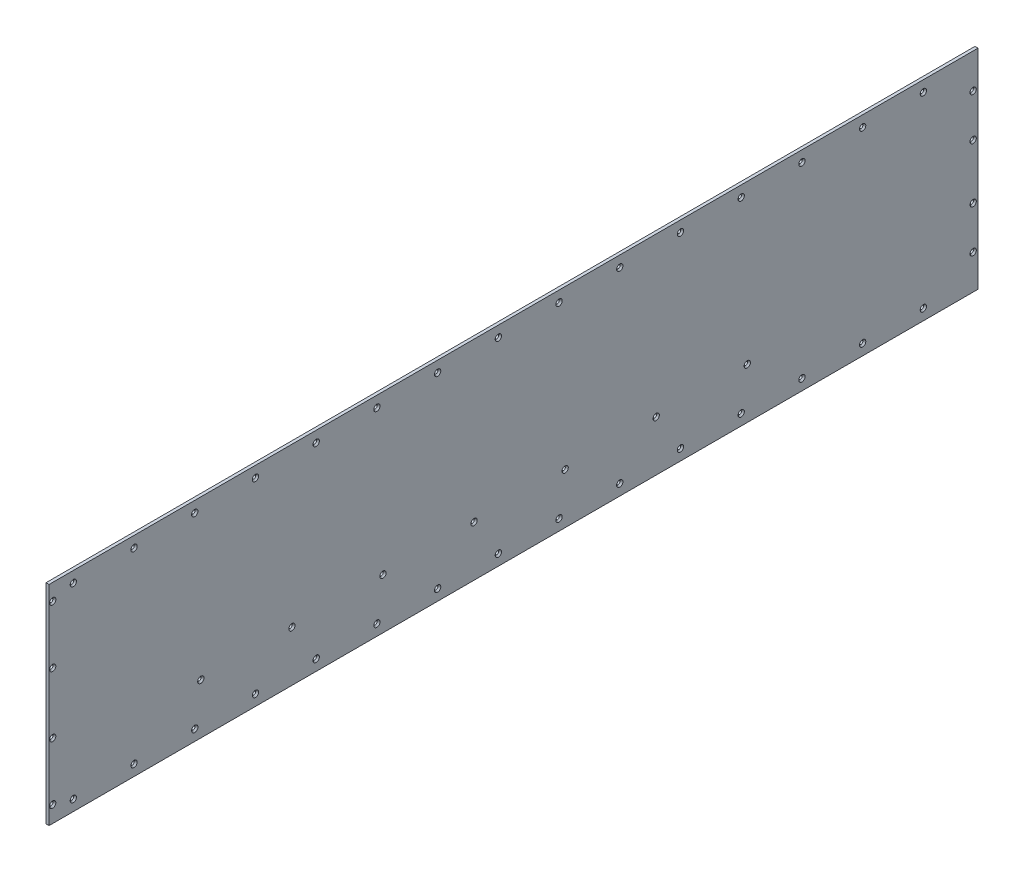
SolidWorks part; units mm, degrees
material "1060 Legierung"
ref_plane "Front Plane" through (0, 0, 0) normal (0, 0, 1) x (1, 0, 0)
ref_plane "Top Plane" through (0, 0, 0) normal (0, 1, 0) x (1, 0, 0)
ref_plane "Right Plane" through (0, 0, 0) normal (1, 0, 0) x (0, 0, -1)
sketch "Sketch1" plane through (0, 0, 0) normal (1, 0, 0) x (0, 0, -1)
  line L0 (0, 0) -> (59.3183, 0) construction
  line L1 (0, 28.1909) -> (0, -28.8956) construction
  line L2 (-765, 172) -> (765, 172)
  line L3 (765, 172) -> (765, -172)
  line L4 (765, -172) -> (-765, -172)
  line L5 (-765, -172) -> (-765, 172)
  dimension "D1" = 1530
  dimension "D2" = 344
extrude "Boss-Extrude1" add sketch "Sketch1" along normal blind 6
chamfer "Fase1" distance 1 angle 45 4 edges at (0, -172, 0) (0, 172, 0) (0, 0, 765) (0, 0, -765)
hole_wizard "CSK for M5 Countersunk Raised Head Screw1" positions "Skizze2" profile "Skizze1" countersink size "M5" standard "DIN" end condition through all
sketch "Skizze2" plane through (6, 0, 0) normal (1, 0, 0) x (0, 0, -1)
  line L0 (802.4859, 0) -> (371.043, 0) construction
  line L2 (765, -172) -> (765, 172) construction
  line L3 (-765, 172) -> (-765, -172) construction
  line L4 (3.3, 0) -> (-3.3, 0) construction
  point P0 (757, 115)
  point P2 (757, 45)
  point P12 (-759, 145)
  point P14 (-759, 50)
  dimension "D1" = 45
  dimension "D2" = 115
  dimension "D3" = 8
  dimension "D4" = 8
  dimension "D5" = 6
  dimension "D6" = 6
  dimension "D7" = 50
  dimension "D8" = 145
sketch "Skizze1" plane through (6, 115, -757) normal (0, 1, 0) x (0, 0, -1)
  line L0 (0, 0) -> (0, 6)
  line L1 (0, 6) -> (2.75, 6)
  line L2 (2.75, 6) -> (2.75, 2.45)
  line L3 (2.75, 2.45) -> (5.2, 0)
  line L5 (5.2, 0) -> (0, 0)
  line L6 (-2.75, 2.45) -> (-5.2, 0) construction
  line L11 (0, -6.35) -> (0, 107.95) construction
  dimension "Bohrerdurchmesser" = 5.5
  dimension "Bohrungstiefe" = 6
  dimension "Senkdurchmesser (Oben)" = 10.4
  dimension "Senkwinkel (Oben)" = 90
hole_wizard "CSK for M5 Countersunk Raised Head Screw2" positions "Sketch3" profile "Sketch2" countersink size "M5" standard "DIN" end condition through all
sketch "Sketch3" plane through (6, 0, 0) normal (1, 0, 0) x (0, 0, -1)
  line L0 (765, 172) -> (-765, 172) construction
  line L1 (-765, 172) -> (-765, -172) construction
  point P0 (-725, 154)
  dimension "D1" = 18
  dimension "D2" = 40
sketch "Sketch2" plane through (6, 154, 725) normal (0, 1, 0) x (0, 0, -1)
  line L0 (0, 0) -> (0, 6)
  line L1 (0, 6) -> (2.75, 6)
  line L2 (2.75, 6) -> (2.75, 2.45)
  line L3 (2.75, 2.45) -> (5.2, 0)
  line L5 (5.2, 0) -> (0, 0)
  line L6 (-2.75, 2.45) -> (-5.2, 0) construction
  line L11 (0, -6.35) -> (0, 107.95) construction
  dimension "Thru Hole Dia." = 5.5
  dimension "Thru Hole Depth" = 6
  dimension "Near C'Sink Dia." = 10.4
  dimension "Near C'Sink Angle" = 90
pattern_linear "LPattern1" count 15 spacing 100 along (0, 0, -1) of "CSK for M5 Countersunk Raised Head Screw2"
mirror "Spiegeln1" about plane through (0, 0, 0) normal (0, 1, 0) of "LPattern1", "CSK for M5 Countersunk Raised Head Screw1", "CSK for M5 Countersunk Raised Head Screw2"
hole_wizard "Formsenkung fur M5 Linsensenkschraube mit Schlitz1" positions "Skizze4" profile "Skizze3" countersink size "M5" standard "Din" end condition through all
sketch "Skizze4" plane through (6, 0, 0) normal (1, 0, 0) x (0, 0, -1)
  line L0 (-765, 172) -> (-765, -172) construction
  line L2 (-765, -172) -> (765, -172) construction
  point P0 (-515, -89)
  dimension "D1" = 250
  dimension "D2" = 83
sketch "Skizze3" plane through (6, -89, 515) normal (0, 1, 0) x (0, 0, -1)
  line L0 (0, 0) -> (0, 6)
  line L1 (0, 6) -> (2.75, 6)
  line L2 (2.75, 6) -> (2.75, 2.45)
  line L3 (2.75, 2.45) -> (5.2, 0)
  line L5 (5.2, 0) -> (0, 0)
  line L6 (-2.75, 2.45) -> (-5.2, 0) construction
  line L11 (0, -6.35) -> (0, 107.95) construction
  dimension "Bohrerdurchmesser" = 5.5
  dimension "Bohrungstiefe" = 6
  dimension "Senkdurchmesser (Oben)" = 10.4
  dimension "Senkwinkel (Oben)" = 90
pattern_linear "Lineares Muster1" count 7 spacing 150 along (0, 0, -1) of "Formsenkung fur M5 Linsensenkschraube mit Schlitz1"
